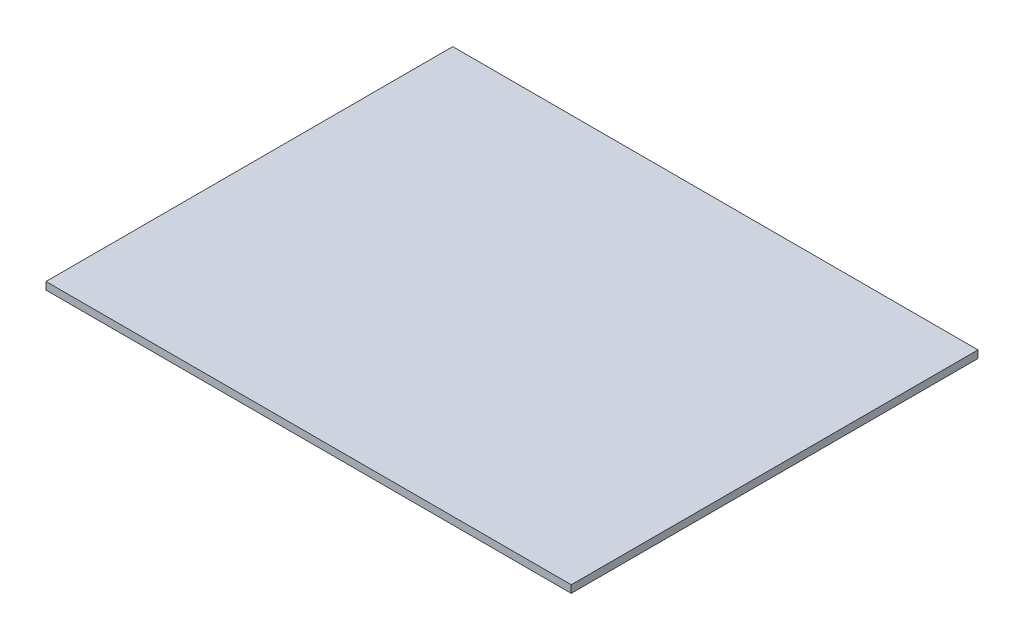
SolidWorks part; units mm, degrees
material "Beech"
ref_plane "Front Plane" through (0, 0, 0) normal (0, 0, 1) x (1, 0, 0)
ref_plane "Top Plane" through (0, 0, 0) normal (0, 1, 0) x (1, 0, 0)
ref_plane "Right Plane" through (0, 0, 0) normal (1, 0, 0) x (0, 0, -1)
sketch "Sketch1" plane through (0, 0, 0) normal (0, 1, 0) x (1, 0, 0)
  line L0 (772, -597.8333) -> (772, 597.8333)
  line L1 (772.5, -598.3333) -> (-772.5, -598.3333) construction
  line L2 (772.5, -598.3333) -> (772.5, 598.3333) construction
  line L3 (772.5, 598.3333) -> (-772.5, 598.3333) construction
  line L4 (-772.5, -598.3333) -> (-772.5, 598.3333) construction
  line L5 (772.5, -598.3333) -> (-772.5, 598.3333) construction
  line L6 (772.5, 598.3333) -> (-772.5, -598.3333) construction
  line L7 (772, 597.8333) -> (-772, 597.8333)
  line L8 (-772, -597.8333) -> (-772, 597.8333)
  line L9 (772, -597.8333) -> (-772, -597.8333)
  point P0 (0, 0)
  dimension "D1" = 1545
  dimension "D2" = 1196.6667
  dimension "D3" = 0.5
extrude "Boss-Extrude1" add sketch "Sketch1" along normal blind 22
equation "\"D2@Sketch1\"=3590/3"
equation "\"D1@Sketch1\"=3090/2"
